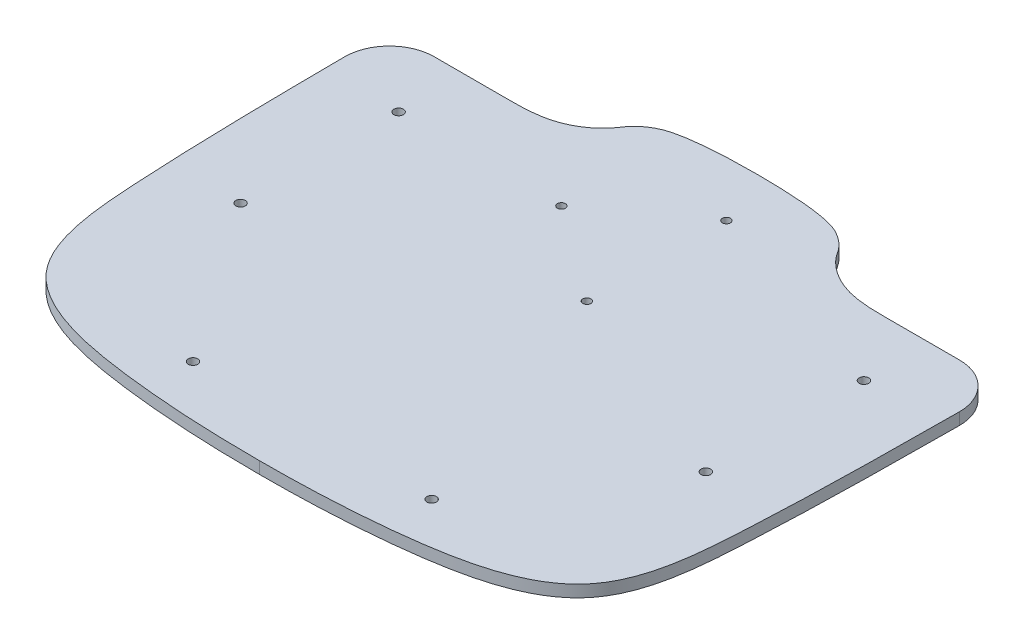
SolidWorks part; units mm, degrees
ref_plane "Front Plane" through (0, 0, 0) normal (0, 0, 1) x (1, 0, 0)
ref_plane "Top Plane" through (0, 0, 0) normal (0, 1, 0) x (1, 0, 0)
ref_plane "Right Plane" through (0, 0, 0) normal (1, 0, 0) x (0, 0, -1)
sketch "Sketch1" plane through (0, 0, 0) normal (0, 1, 0) x (1, 0, 0)
  line L1 (-120, 155) -> (120, 155)
  line L2 (-120, 155) -> (-120, -155)
  line L3 (-120, -155) -> (120, -155)
  line L4 (120, 155) -> (120, -155)
  point P4 (0, 155)
  point P6 (-120, 0)
  dimension "D1" = 240
  dimension "D2" = 310
extrude "Boss-Extrude1" add sketch "Sketch1" along normal blind 4 contours L2 L1 L4 L3
sketch "Sketch2" plane through (0, 4, 0) normal (0, 1, 0) x (1, 0, 0)
  line L0 (-120, 155) -> (120, 155) construction
  line L1 (-120, 0) -> (120, 0)
  line L2 (-120, 155) -> (-120, -155) construction
  circle B0 centre (49, -30) radius 1.75
  circle B1 centre (-49, -30) radius 1.75
  circle B2 centre (-88.957, -132.3382) radius 1.75
  circle B3 centre (0, -146) radius 1.75
  circle B4 centre (88.957, -132.3382) radius 1.75
  circle B5 centre (110.4185, 44.9345) radius 1.75
  circle B6 centre (88.957, 132.3382) radius 1.75
  circle B7 centre (0, 146) radius 1.75
  circle B8 centre (-88.957, 132.3382) radius 1.75
  circle B9 centre (-110.4185, 44.9345) radius 1.75
  spline B10 degree 3 poles (0, 155) (30.5722, 155) (80.3433, 153.7333) (119.2212, 117.6544) (120, 45.41) (120, 0) knots 0 0 0 0 0.458017 0.558017 1 1 1 1
  spline B11 degree 3 poles (0, 155) (-30.5722, 155) (-80.3433, 153.7333) (-119.2212, 117.6544) (-120, 45.41) (-120, 0) knots 0 0 0 0 0.458017 0.558017 1 1 1 1
  spline B12 degree 3 poles (0, -155) (30.5722, -155) (80.3433, -153.7333) (119.2212, -117.6544) (120, -45.41) (120, 0) knots 0 0 0 0 0.458017 0.558017 1 1 1 1
  spline B13 degree 3 poles (0, -155) (-30.5722, -155) (-80.3433, -153.7333) (-119.2212, -117.6544) (-120, -45.41) (-120, 0) knots 0 0 0 0 0.458017 0.558017 1 1 1 1
  line M2 (-120, -155) -> (120, -155)
  line M3 (120, -155) -> (120, 155)
  line M5 (-120, 155) -> (-120, -155)
sketch_block_instance "Base-2-F1-1"
sketch_block "Base-2-F1"
extrude "Cut-Extrude1" cut sketch "Sketch2" against normal up to next contours B13 M2 M5 | B12 M2 M3 | B0 | B2 | B3 | B5
sketch "Sketch3" plane through (0, 4, 0) normal (0, 1, 0) x (1, 0, 0)
  line L5 (-120, 0) -> (120, 0)
  line L6 (-120, 0) -> (-120, 155)
  line L7 (-120, 155) -> (120, 155)
  line L8 (120, 0) -> (120, 155)
  point P4 (0, 0)
  line M23 (120, 0) -> (120, 155)
  line M24 (120, 155) -> (-120, 155)
  line M25 (-120, 155) -> (-120, 0)
  dimension "D1" = 240
  dimension "D2" = 155
extrude "Cut-Extrude2" cut sketch "Sketch3" against normal through all contours L5 M25 M23 M24
sketch "Sketch14" plane through (0, 4, 0) normal (0, 1, 0) x (1, 0, 0)
  line L0 (0, 0) -> (0, -155) construction
  circle A0 centre (78, -75) radius 1.6
  circle A1 centre (78, -22) radius 1.6
  circle A2 centre (40, -128.95) radius 1.6
  circle A3 centre (-40, -128.95) radius 1.6
  circle A4 centre (-78, -75) radius 1.6
  circle A5 centre (-78, -22) radius 1.6
  point P3 (0, -155)
  dimension "D1" = 3.2
  dimension "D2" = 80
  dimension "D3" = 78
  dimension "D4" = 26.05
  dimension "D5" = 40
  dimension "D6" = 53
extrude "Cut-Extrude10" cut sketch "Sketch14" against normal through all
sketch "Sketch16" plane through (0, 4, 0) normal (0, 1, 0) x (1, 0, 0)
  line L0 (0, 0) -> (0, 20) construction
  line L1 (-120, 0) -> (120, 0) construction
  line L2 (-62.5, 0) -> (62.5, 0)
  spline S0 degree 3 poles (-62.5, 0) (-56.8593, 0) (-47.5669, 0.7193) (-37.2478, 7.965) (-35.0117, 13.7063) (-25.1741, 19.0991) (-11.4615, 20) (0, 20) knots 0 0 0 0 0.283629 0.580943 0.775948 0.817853 1 1 1 1
  spline S1 degree 3 poles (62.5, 0) (56.8593, 0) (47.5669, 0.7193) (37.2478, 7.965) (35.0117, 13.7063) (25.1741, 19.0991) (11.4615, 20) (0, 20) knots 0 0 0 0 0.283629 0.580943 0.775948 0.817853 1 1 1 1
  dimension "D1" = 20
  dimension "D2" = 125
extrude "Boss-Extrude3" add sketch "Sketch16" against normal through all
sketch "Sketch17" plane through (0, 4, 0) normal (0, 1, 0) x (1, 0, 0)
  line L0 (103.1101, 0) -> (120, 0)
  line L1 (0, 0) -> (0, -155) construction
  line L2 (62.5, 0) -> (120, 0) construction
  line L3 (-103.1101, 0) -> (-120, 0)
  spline S0 degree 3 poles (0, -146.5903) (13.4599, -146.5903) (46.7542, -145.6395) (97.9604, -134.5675) (102.1242, -80.8714) (102.9233, -39.7469) (103.1101, -11.5683) (103.1101, 0) knots 0 0 0 0 0.214535 0.423704 0.615344 0.849411 1 1 1 1
  spline S1 degree 3 poles (3776.8914, -1471.0236) (-829.8159, 142.6806) (-7.3014, -235.0683) (192.2778, -49.8573) (-118.5349, 1088.9492) (1073.8625, -3883.9573) knots -2.254362 -2.254362 -2.254362 -2.254362 0.458017 0.558017 2.879133 2.879133 2.879133 2.879133 only from (0, -155) to (120, 0) construction
  spline S2 degree 3 poles (0, -155) (30.5722, -155) (80.3433, -153.7333) (119.2212, -117.6544) (120, -45.41) (120, 0) knots 0 0 0 0 0.458017 0.558017 1 1 1 1
  spline S3 degree 3 poles (0, -155) (-30.5722, -155) (-80.3433, -153.7333) (-119.2212, -117.6544) (-120, -45.41) (-120, 0) knots 0 0 0 0 0.458017 0.558017 1 1 1 1
  spline S4 degree 3 poles (0, -146.5903) (-13.4599, -146.5903) (-46.7542, -145.6395) (-97.9604, -134.5675) (-102.1242, -80.8714) (-102.9233, -39.7469) (-103.1101, -11.5683) (-103.1101, 0) knots 0 0 0 0 0.214535 0.423704 0.615344 0.849411 1 1 1 1
extrude "Cut-Extrude11" cut sketch "Sketch17" against normal through all
fillet "Fillet2" radius 15 2 edges at (103.1101, 2, 0) (-103.1101, 2, 0)
sketch "Sketch18" plane through (0, 4, 0) normal (0, 1, 0) x (1, 0, 0)
  line L0 (8.5, 1.4) -> (8.5, -45.4) construction
  line L1 (-23.42, -22) -> (8.5, -22) construction
  circle A0 centre (8.5, 1.4) radius 1.35
  circle A1 centre (8.5, -45.4) radius 1.35
  circle A2 centre (-23.42, -22) radius 1.35
  point P6 (78, -22)
  dimension "D1" = 2.7
  dimension "D2" = 46.8
  dimension "D3" = 31.92
  dimension "D4" = 69.5
  dimension "D5" = 22
extrude "Cut-Extrude12" cut sketch "Sketch18" against normal blind 10
